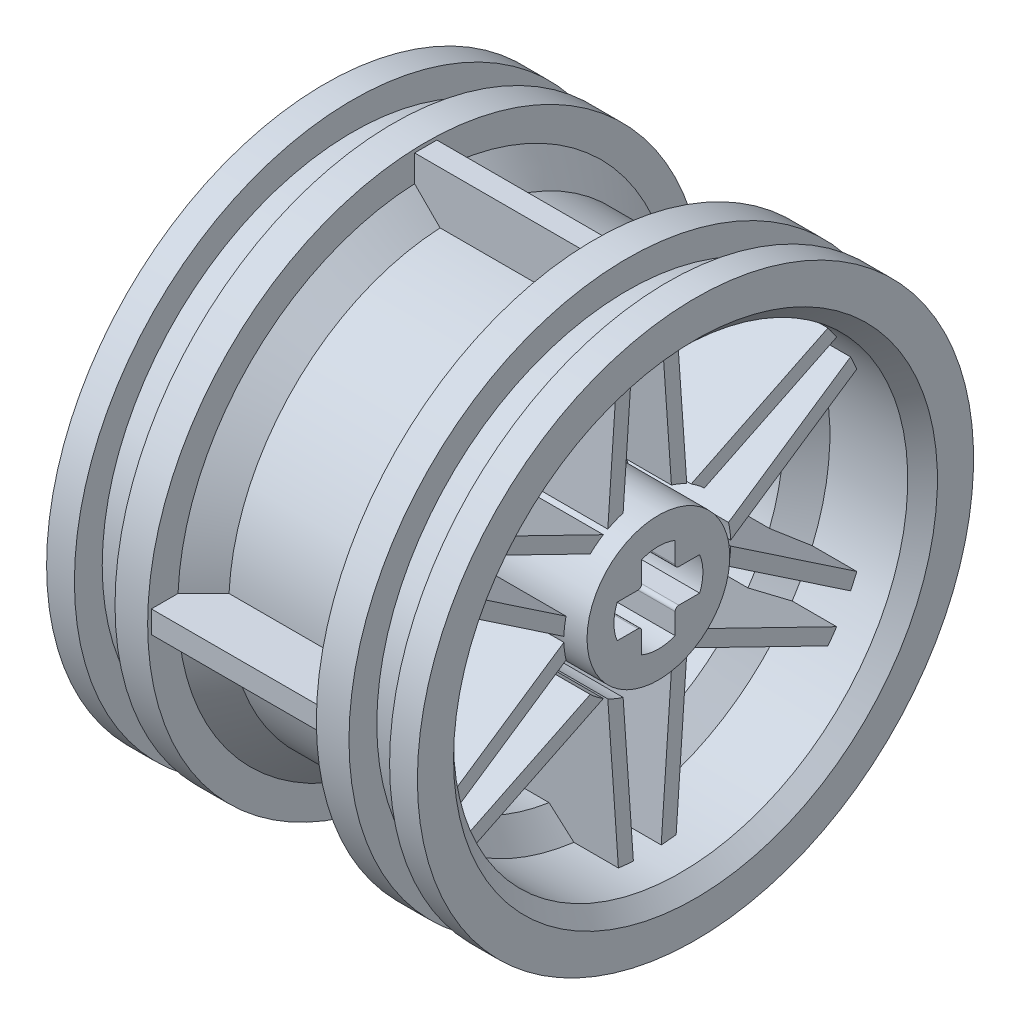
SolidWorks part; units mm, degrees
ref_plane "Front Plane" through (0, 0, 0) normal (0, 0, 1) x (1, 0, 0)
ref_plane "Top Plane" through (0, 0, 0) normal (0, 1, 0) x (1, 0, 0)
ref_plane "Right Plane" through (0, 0, 0) normal (1, 0, 0) x (0, 0, -1)
sketch "Sketch1" plane through (0, 0, 0) normal (0, 0, 1) x (1, 0, 0)
  line L0 (0, 0) -> (17.2681, 0) construction
  line L1 (0, 0) -> (0, 54.0426) construction
  line L2 (10, 12.25) -> (10, 15)
  line L3 (10, 15) -> (8.5, 15)
  line L4 (8.5, 15) -> (8.5, 13.5)
  line L5 (8.5, 13.5) -> (6.31, 13.5)
  line L6 (6.31, 13.5) -> (6.31, 15)
  line L7 (6.31, 15) -> (4.55, 15)
  line L8 (4.55, 15) -> (4.55, 13.375)
  line L9 (4.55, 13.375) -> (3.175, 12)
  line L10 (3.175, 12) -> (-3.175, 12)
  line L11 (-4.55, 13.375) -> (-3.175, 12)
  line L12 (-4.55, 15) -> (-4.55, 13.375)
  line L13 (-6.31, 15) -> (-4.55, 15)
  line L14 (-6.31, 13.5) -> (-6.31, 15)
  line L15 (-8.5, 13.5) -> (-6.31, 13.5)
  line L16 (-8.5, 15) -> (-8.5, 13.5)
  line L17 (-10, 15) -> (-8.5, 15)
  line L18 (-10, 12.25) -> (-10, 15)
  line L19 (-10, -12.25) -> (-10, -15) construction
  line L20 (-10, -15) -> (-8.5, -15) construction
  line L21 (-8.5, -15) -> (-8.5, -13.5) construction
  line L22 (-8.5, -13.5) -> (-6.31, -13.5) construction
  line L23 (-6.31, -13.5) -> (-6.31, -15) construction
  line L24 (-6.31, -15) -> (-4.55, -15) construction
  line L25 (-4.55, -15) -> (-4.55, -13.375) construction
  line L26 (-4.55, -13.375) -> (-3.175, -12) construction
  line L27 (3.175, -12) -> (-3.175, -12) construction
  line L28 (4.55, -13.375) -> (3.175, -12) construction
  line L29 (4.55, -15) -> (4.55, -13.375) construction
  line L30 (6.31, -15) -> (4.55, -15) construction
  line L31 (6.31, -13.5) -> (6.31, -15) construction
  line L32 (8.5, -13.5) -> (6.31, -13.5) construction
  line L33 (8.5, -15) -> (8.5, -13.5) construction
  line L34 (10, -15) -> (8.5, -15) construction
  line L35 (10, -12.25) -> (10, -15) construction
  line L36 (10, 12.25) -> (5, 12.25)
  line L37 (-10, 12.25) -> (-5, 12.25)
  line L38 (3.75, 11) -> (-3.75, 11)
  line L39 (3.75, -11) -> (-3.75, -11) construction
  line L40 (5, 12.25) -> (3.75, 11)
  line L41 (-5, 12.25) -> (-3.75, 11)
  point P15 (0, 12)
  dimension "D1" = 6.35
  dimension "D2" = 9.1
  dimension "D3" = 2.19
  dimension "D4" = 20
  dimension "D5" = 1.5
  dimension "D6" = 30
  dimension "D7" = 24
  dimension "D8" = 27
  dimension "D9" = 45
  dimension "D10" = 24.5
  dimension "D11" = 5
  dimension "D12" = 22
revolve "Revolve1" add sketch "Sketch1" angle 360 about L0
sketch "Sketch2" plane through (0, 0, 0) normal (0, 0, 1) x (1, 0, 0)
  line L0 (1, 11) -> (2.37, 11)
  line L1 (3.75, 11) -> (-3.75, 11) construction
  line L2 (1, 11) -> (-0.6481, 5.8)
  line L3 (-0.6481, 5.8) -> (-3.4, 5.8)
  line L4 (-3.4, 5.8) -> (-3.4, 3.805)
  line L5 (-3.4, 3.805) -> (0.6, 3.805)
  line L6 (0.6, 3.805) -> (0.6, 0)
  line L7 (0.6, 0) -> (8, 0)
  line L8 (0, 0) -> (17.2681, 0) construction
  line L9 (0, 0) -> (18.7142, 0) construction
  line L10 (8, 0) -> (8, 3.85)
  line L11 (8, 3.85) -> (2, 3.85)
  line L12 (2, 3.85) -> (2, 4.5)
  line L13 (2, 4.5) -> (0.5, 4.5)
  line L14 (0.5, 4.5) -> (0.5, 5.1)
  line L15 (0.5, 5.1) -> (2.37, 11)
  line L16 (-10, 12.25) -> (-10, 15) construction
  line L17 (10, 12.25) -> (10, 15) construction
  line L18 (8, -3.85) -> (2, -3.85) construction
  line L19 (2, -4.5) -> (0.5, -4.5) construction
  line L20 (-0.6481, -5.8) -> (-3.4, -5.8) construction
  dimension "D1" = 6.6
  dimension "D2" = 7.63
  dimension "D3" = 11
  dimension "D4" = 11.6
  dimension "D5" = 1.995
  dimension "D6" = 4
  dimension "D7" = 8
  dimension "D8" = 7.7
  dimension "D9" = 2
  dimension "D10" = 9
  dimension "D11" = 1.5
  dimension "D12" = 0.6
revolve "Revolve3" add sketch "Sketch2" angle 360 about L9
sketch "Sketch3" plane through (-3.4, 0, 0) normal (-1, 0, 0) x (0, 0, 1)
  circle A0 centre (0, -6) radius 1.45
  dimension "D1" = 2.9
  dimension "D2" = 6
extrude "Boss-Extrude1" add sketch "Sketch3" against normal up to next
sketch "Sketch4" plane through (-3.4, 0, 0) normal (-1, 0, 0) x (0, 0, 1)
  line L0 (0, 0) -> (0, 2.4395) construction
  circle A0 centre (0, 4.75) radius 0.6
  circle A1 centre (0, 0) radius 4.75 construction
  circle A2 centre (2.8024, 3.8352) radius 0.6
  circle A3 centre (4.5254, 1.4432) radius 0.6
  circle A4 centre (4.5054, -1.5046) radius 0.6
  circle A5 centre (2.75, -3.873) radius 0.6
  circle A6 centre (-0.0646, -4.7496) radius 0.6 [skipped]
  circle A7 centre (-2.75, -3.873) radius 0.6
  circle A8 centre (-4.5054, -1.5046) radius 0.6
  circle A9 centre (-2.8024, 3.8352) radius 0.6
  circle A10 centre (-4.5254, 1.4432) radius 0.6
  circle A12 centre (0, -6) radius 1
  arc A13 (-1.4015, -5.6281) -> (1.4015, -5.6281) centre (0, -6) ccw construction
  point P29 (0, 0)
  dimension "D1" = 9.5
  dimension "D2" = 1.2
  dimension "D4" = 2
  dimension "D5" = 5.5
  dimension "D3" = 6
extrude "Cut-Extrude1" cut sketch "Sketch4" against normal blind 0.2
sketch "Sketch5" plane through (8, 0, 0) normal (1, 0, 0) x (0, 0, -1)
  line L0 (0, 6.2514) -> (0, 0) construction
  line L1 (0, 0) -> (7.5877, 0) construction
  line L2 (0.9, 1.1) -> (0.9, 2.2249)
  line L3 (-0.9, 1.1) -> (-0.9, 2.2249)
  line L4 (1.1, -0.9) -> (2.2249, -0.9)
  line L5 (1.1, 0.9) -> (2.2249, 0.9)
  line L6 (-0.9, -1.1) -> (-0.9, -2.2249)
  line L7 (0.9, -1.1) -> (0.9, -2.2249)
  line L8 (-1.1, 0.9) -> (-2.2249, 0.9)
  line L9 (-1.1, -0.9) -> (-2.2249, -0.9)
  arc A0 (0.9, 2.2249) -> (-0.9, 2.2249) centre (0, 0) ccw
  arc A1 (2.2249, -0.9) -> (2.2249, 0.9) centre (0, 0) ccw
  arc A2 (-0.9, -2.2249) -> (0.9, -2.2249) centre (0, 0) ccw
  arc A3 (-2.2249, 0.9) -> (-2.2249, -0.9) centre (0, 0) ccw
  arc A4 (1.1, 0.9) -> (0.9, 1.1) centre (1.1, 1.1) cw
  arc A5 (-1.1, 0.9) -> (-0.9, 1.1) centre (-1.1, 1.1) ccw
  arc A6 (-1.1, -0.9) -> (-0.9, -1.1) centre (-1.1, -1.1) cw
  arc A7 (1.1, -0.9) -> (0.9, -1.1) centre (1.1, -1.1) ccw
  circle A8 centre (0, 0) radius 3.4567 construction
  point P27 (0, 0)
  dimension "D3" = 0.2
  dimension "D2" = 2.4
  dimension "D1" = 1.8
extrude "Cut-Extrude2" cut sketch "Sketch5" against normal up to next
sketch "Sketch6" plane through (10, 0, 0) normal (1, 0, 0) x (0, 0, -1)
  line L0 (0, 17.5556) -> (0, 0) construction
  line L1 (0, 0) -> (8, 0) construction
  circle A0 centre (4, 6.9282) radius 1.5
  circle A1 centre (8, 0) radius 1.5
  circle A2 centre (4, -6.9282) radius 1.5
  circle A3 centre (-4, -6.9282) radius 1.5
  circle A4 centre (-8, 0) radius 1.5
  circle A5 centre (-4, 6.9282) radius 1.5
  point P19 (0, 0)
  dimension "D2" = 3
  dimension "D3" = 16
  dimension "D1" = 6
extrude "Cut-Extrude3" cut sketch "Sketch6" against normal through all
sketch "Sketch7" plane through (0, 0, 0) normal (0, 0, 1) x (1, 0, 0)
  line L0 (4.55, 14.8) -> (-4.55, 14.8)
  line L1 (4.55, 15) -> (4.55, -15) construction
  line L2 (-4.55, -15) -> (-4.55, 15) construction
  line L3 (0, 0) -> (15.194, 0) construction
  line L4 (4.55, -14.8) -> (-4.55, -14.8) construction
  dimension "D1" = 29.6
rib "Rib1" sketch "Sketch7" sketch "Sketch7" thickness 1.2 extrusion direction parallel to sketch draft on no parameters "D1"=1.2
pattern_circular "CirPattern1" count 4 over 360 about axis through (0, 0, 0) along (1, 0, 0) of "Rib1"
sketch "Sketch8" plane through (10, 0, 0) normal (1, 0, 0) x (0, 0, -1)
  line L0 (1.5573, 12.1506) -> (2.129, 3.9645)
  line L1 (1.3031, 4.3072) -> (0.75, 12.227)
  line L2 (0, 0) -> (0, 17.7652) construction
  line L3 (-1.3031, 4.3072) -> (-0.75, 12.227)
  line L4 (-1.5573, 12.1506) -> (-2.129, 3.9645)
  circle A0 centre (0, 0) radius 12.25 construction
  arc A2 (2.129, 3.9645) -> (1.3031, 4.3072) centre (0, 0) ccw
  arc A3 (-1.5573, 12.1506) -> (-0.75, 12.227) centre (0, 0) cw
  arc A4 (-2.129, 3.9645) -> (-1.3031, 4.3072) centre (0, 0) cw
  arc A5 (1.5573, 12.1506) -> (0.75, 12.227) centre (0, 0) ccw
  arc A6 (2.2249, -0.9) -> (2.2249, 0.9) centre (0, 0) ccw construction
  circle A7 centre (0, 0) radius 4.5 construction
  dimension "D1" = 0.8
  dimension "D2" = 1.5
extrude "Boss-Extrude2" add sketch "Sketch8" against normal up to next from offset 2.6 offset against normal yes
pattern_circular "CirPattern2" count 6 over 360 about axis through (0, 0, 0) along (1, 0, 0) of "Boss-Extrude2"
chamfer "Chamfer1" distance 0.8 angle 45 2 edges at (-10, 0, 12.25) (10, 0, 12.25)
